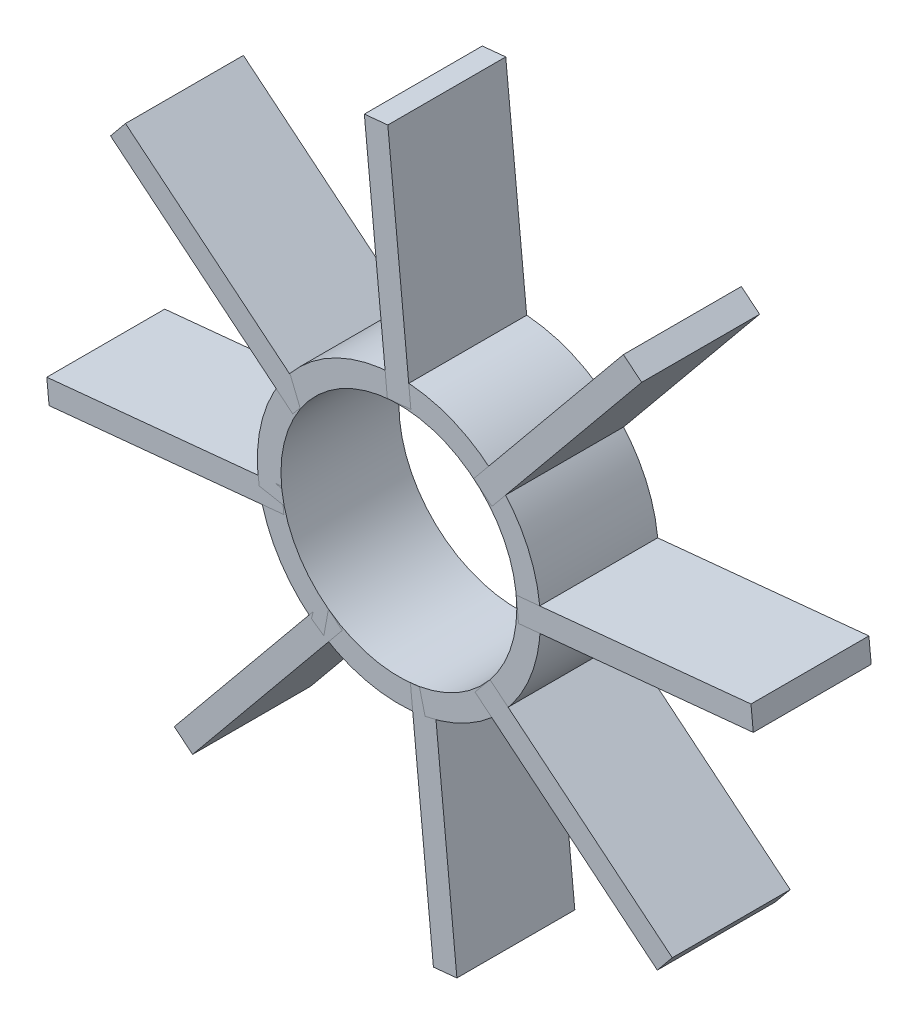
SolidWorks part; units mm, degrees
ref_plane "Front Plane" through (0, 0, 0) normal (0, 0, 1) x (1, 0, 0)
ref_plane "Top Plane" through (0, 0, 0) normal (0, 1, 0) x (1, 0, 0)
ref_plane "Right Plane" through (0, 0, 0) normal (1, 0, 0) x (0, 0, -1)
sketch "Sketch1" plane through (0, 0, 0) normal (0, 0, 1) x (1, 0, 0)
  line L0 (-149.2834, -14.6443) -> (-49.7611, -4.8814)
  line L1 (14.6443, -149.2834) -> (4.8814, -49.7611)
  line L2 (-115.9144, 95.2042) -> (-38.6381, 31.7347)
  line L3 (-95.2042, -115.9144) -> (-31.7347, -38.6381)
  line L4 (-4.8814, 49.7611) -> (-14.6443, 149.2834)
  line L5 (31.7347, 38.6381) -> (95.2042, 115.9144)
  line L6 (49.7611, 4.8814) -> (149.2834, 14.6443)
  line L7 (38.6381, -31.7347) -> (115.9144, -95.2042)
  circle A1 centre (0, 0) radius 50
  point P1 (0, 0)
  point P7 (0, 0)
  point P10 (0, 0)
  point P13 (0, 0)
  point P15 (0, 0)
  point P24 (0, 0)
  dimension "D1" = 45
  dimension "D2" = 45
  dimension "D3" = 45
  dimension "D4" = 50
  dimension "D5" = 150
  dimension "D6" = 150
  dimension "D7" = 150
  dimension "D8" = 150
  dimension "D9" = 150
  dimension "D10" = 150
  dimension "D11" = 150
  dimension "D12" = 150
extrude "Extrude-Thin1" add sketch "Sketch1" along normal blind 50 thin
